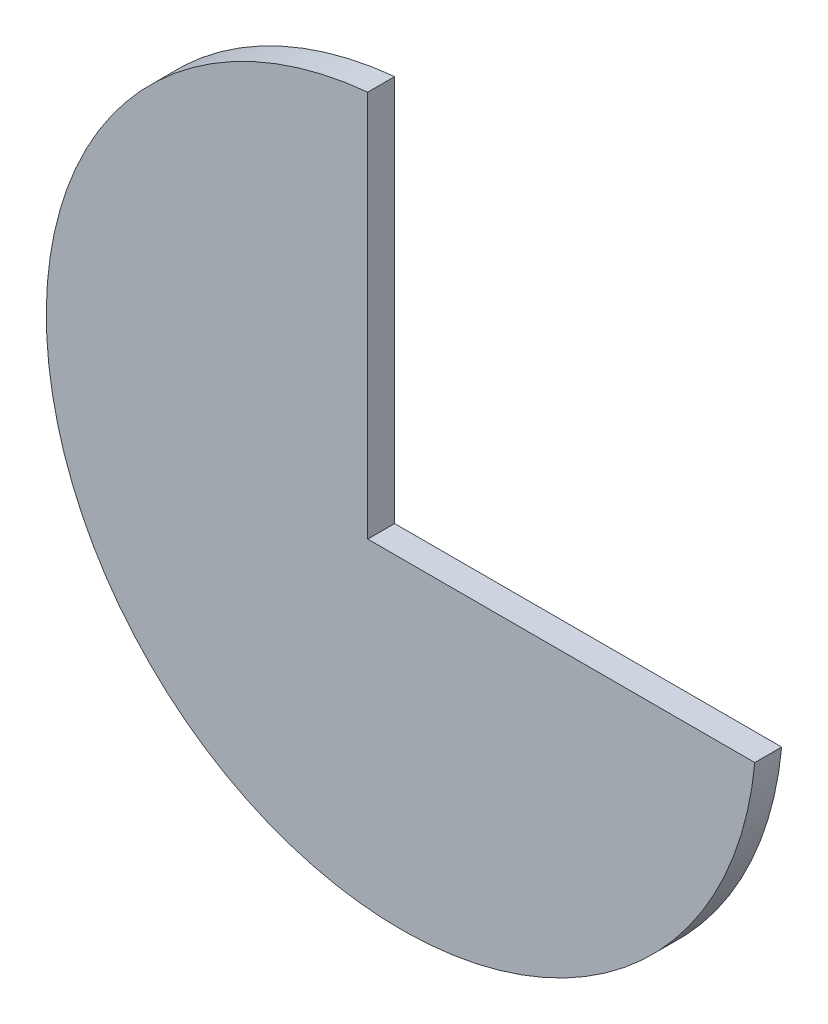
SolidWorks part; units mm, degrees
ref_plane "Front Plane" through (0, 0, 0) normal (0, 0, 1) x (1, 0, 0)
ref_plane "Top Plane" through (0, 0, 0) normal (0, 1, 0) x (1, 0, 0)
ref_plane "Right Plane" through (0, 0, 0) normal (1, 0, 0) x (0, 0, -1)
sketch "Sketch2" plane through (0, 0, 0) normal (0, 0, 1) x (1, 0, 0)
  line L0 (-0.0489, -0.285) -> (0.0489, -0.285)
  line L1 (-0.0489, -0.26) -> (0.0489, -0.26)
  line L2 (0, 0) -> (0.2892, 0) construction
  line L3 (0, 0.2892) -> (0, 0) construction
  line L4 (-0.025, -0.025) -> (0.263, -0.025)
  line L6 (-0.025, 0.263) -> (-0.025, -0.025)
  arc A0 (0, 0.2892) -> (0.2892, 0) centre (0, 0) ccw construction
  arc A1 (-0.025, 0.263) -> (0.263, -0.025) centre (0, 0) ccw
  point P0 (0, 0)
  dimension "D1" = 0.025
sketch "Sketch1" plane through (0, 0, 0) normal (1, 0, 0) x (0, 0, -1)
  line L0 (-0.025, 0.2899) -> (0.025, 0.2899)
  arc A0 (0.025, 0.2899) -> (-0.025, 0.2899) centre (0, 0.2899) ccw
  dimension "D1" = 0.05
extrude "Boss-Extrude1" add sketch "Sketch2" along normal mid plane 0.02 contours A1 L4 L6
